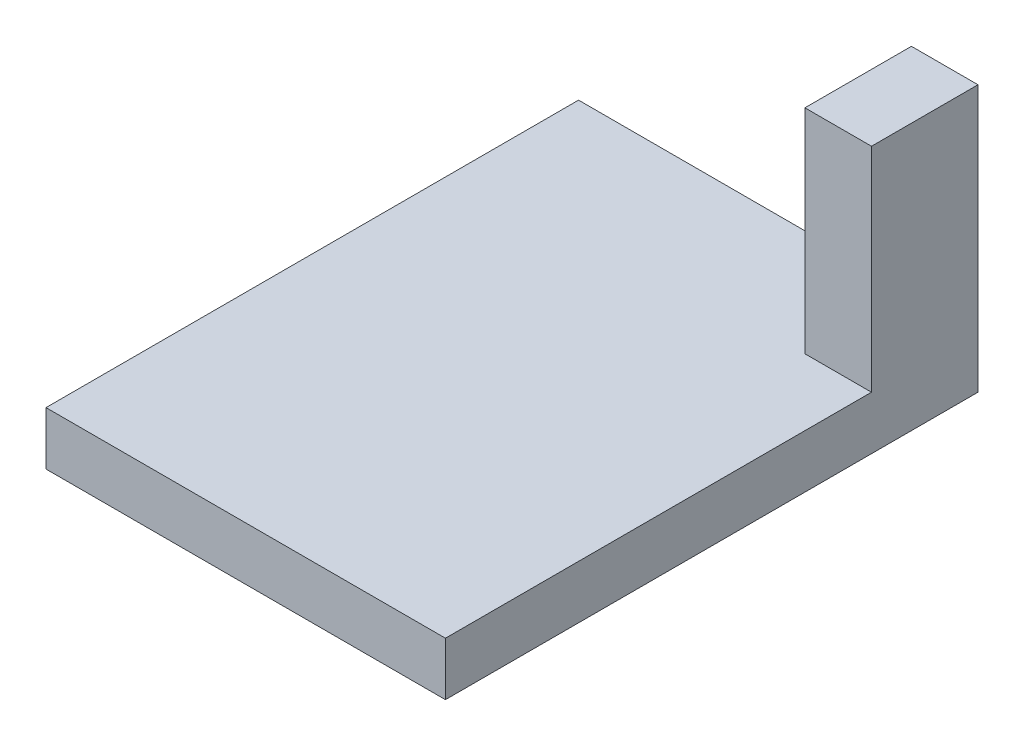
SolidWorks part; units mm, degrees
ref_plane "前视基准面" through (0, 0, 0) normal (0, 0, 1) x (1, 0, 0)
ref_plane "上视基准面" through (0, 0, 0) normal (0, 1, 0) x (1, 0, 0)
ref_plane "右视基准面" through (0, 0, 0) normal (1, 0, 0) x (0, 0, -1)
sketch "草图1" plane through (0, 0, 0) normal (0, 1, 0) x (1, 0, 0)
  line L1 (0, 0) -> (2.5, 0)
  line L2 (0, 0) -> (0, 4)
  line L3 (0, 4) -> (2.5, 4)
  line L4 (2.5, 0) -> (2.5, 4)
  dimension "D1" = 4
  dimension "D2" = 2.5
extrude "凸台-拉伸1" add sketch "草图1" along normal blind 8
sketch "草图2" plane through (0, 0, 0) normal (0, -1, 0) x (1, 0, 0)
  line L1 (2.5, -4) -> (-12.5, -4)
  line L2 (2.5, -4) -> (2.5, 16)
  line L3 (2.5, 16) -> (-12.5, 16)
  line L4 (-12.5, -4) -> (-12.5, 16)
  dimension "D1" = 15
  dimension "D2" = 20
extrude "凸台-拉伸2" add sketch "草图2" along normal blind 2
